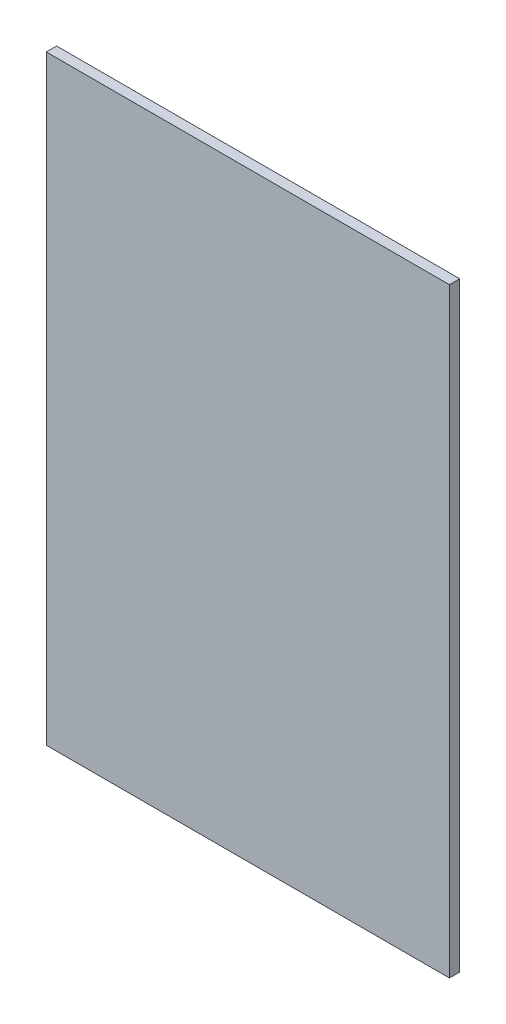
SolidWorks part; units mm, degrees
ref_plane "Front Plane" through (0, 0, 0) normal (0, 0, 1) x (1, 0, 0)
ref_plane "Top Plane" through (0, 0, 0) normal (0, 1, 0) x (1, 0, 0)
ref_plane "Right Plane" through (0, 0, 0) normal (1, 0, 0) x (0, 0, -1)
sketch "Sketch1" plane through (0, 0, 0) normal (0, 0, 1) x (1, 0, 0)
  line L1 (-235, -350) -> (235, -350)
  line L2 (-235, -350) -> (-235, 350)
  line L3 (-235, 350) -> (235, 350)
  line L4 (235, -350) -> (235, 350)
  line L5 (-235, -350) -> (235, 350) construction
  line L6 (-235, 350) -> (235, -350) construction
  point P0 (0, 0)
  dimension "D1" = 470
  dimension "D2" = 700
extrude "Boss-Extrude1" add sketch "Sketch1" along normal blind 12
equation "\"Case_Depth\" = 470mm"
equation "\"WoodSheet_Thickness\" = 12mm"
equation "\"D1@Sketch1\"=\"Case_Depth\""
equation "\"D1@Boss-Extrude1\"=\"WoodSheet_Thickness\""
equation "\"Case_Width\" = 750mm"
equation "\"Case_Height\" = 700mm"
equation "\"D2@Sketch1\"=\"Case_Height\""
